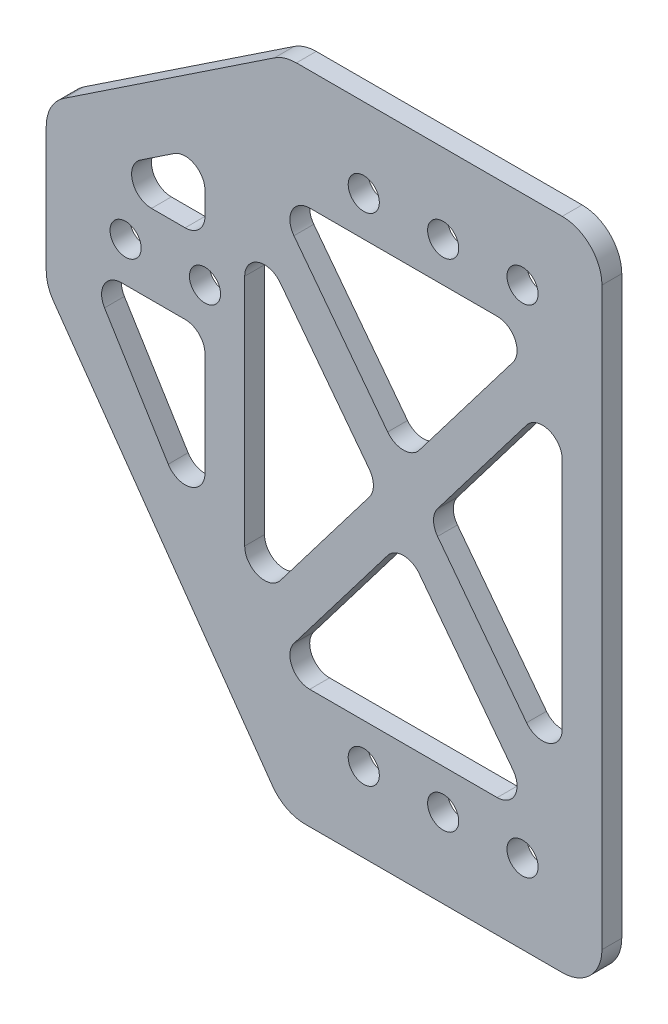
SolidWorks part; units mm, degrees
material "6061-T6 (SS)"
ref_plane "Front Plane" through (0, 0, 0) normal (0, 0, 1) x (1, 0, 0)
ref_plane "Top Plane" through (0, 0, 0) normal (0, 1, 0) x (1, 0, 0)
ref_plane "Right Plane" through (0, 0, 0) normal (1, 0, 0) x (0, 0, -1)
sketch "Sketch1" plane through (0, 0, 0) normal (0, 0, 1) x (1, 0, 0)
  line L0 (0, 25.4) -> (38.1, 50.8)
  line L1 (0, 0) -> (38.1, 0)
  line L2 (0, 0) -> (0, 25.4)
  line L3 (0, 25.4) -> (38.1, 25.4)
  line L4 (38.1, 0) -> (38.1, 25.4)
  line L5 (88.9, 50.8) -> (38.1, 50.8)
  line L6 (88.9, 50.8) -> (88.9, -53.975)
  line L7 (88.9, -53.975) -> (38.1, -53.975)
  line L8 (38.1, 50.8) -> (38.1, -53.975)
  line L9 (38.1, 46.9841) -> (5.7238, 25.4)
  line L10 (0, 0) -> (38.1, -53.975)
  line L11 (3.8863, 0) -> (38.1, -48.4694)
  line L12 (50.8, -41.275) -> (76.2, -41.275) construction
  circle A0 centre (12.7, 12.7) radius 2.4892
  circle A1 centre (25.4, 12.7) radius 2.4892
  circle A5 centre (50.8, 38.1) radius 2.4892
  circle A6 centre (63.5, 38.1) radius 2.4892
  circle A7 centre (76.2, 38.1) radius 2.4892
  circle A8 centre (50.8, -41.275) radius 2.4892
  circle A9 centre (76.2, -41.275) radius 2.4892
  circle A10 centre (63.5, -41.275) radius 2.4892
  circle A11 centre (63.5, 12.7) radius 2.4892 [skipped]
  circle A12 centre (50.8, 12.7) radius 2.4892 [skipped]
  circle A13 centre (38.1, 12.7) radius 2.4892 [skipped]
  point P16 (51.4809, 25.4)
  point P17 (19.05, -26.9875)
  dimension "D3" = 4.9784
  dimension "D4" = 12.7
  dimension "D5" = 12.7
  dimension "D7" = 12.7
  dimension "D10" = 4.9784
  dimension "D12" = 12.7
  dimension "D20" = 12.7
  dimension "D21" = 4.9784
  dimension "D2" = 25.4
  dimension "D8" = 50.8
  dimension "D9" = 25.4
  dimension "D11" = 12.7
  dimension "D13" = 12.7
  dimension "D14" = 12.7
  dimension "D15" = 3.175
  dimension "D16" = 53.975
  dimension "D17" = 3.175
  dimension "D18" = 12.7
  dimension "D19" = 25.4
  dimension "D22" = 38.1
  dimension "D6" = 5
extrude "Boss-Extrude1" add sketch "Sketch1" along normal blind 3.175
fillet "Fillet1" radius 6.35 6 edges at (0, 0, 1.5875) (0, 25.4, 1.5875) (38.1, 50.8, 1.5875) (88.9, -53.975, 1.5875) (38.1, -53.975, 1.5875) (88.9, 50.8, 1.5875)
sketch "Sketch2" plane through (0, 0, 0) normal (0, 0, 1) x (1, 0, 0)
  line L0 (31.75, 31.75) -> (82.55, -34.925) construction
  line L1 (82.55, 31.75) -> (31.75, -34.925) construction
  line L2 (31.75, 26.5111) -> (80.0245, -36.8492)
  line L3 (80.0245, 33.6742) -> (29.2245, -33.0008)
  line L4 (35.7415, 31.75) -> (85.0755, -33.0008)
  line L5 (85.0755, 29.8258) -> (34.2755, -36.8492)
  line L6 (29.2245, 29.8258) -> (80.0245, -36.8492) construction
  line L7 (34.2755, 33.6742) -> (85.0755, -33.0008) construction
  line L8 (31.75, -34.925) -> (6.35, 6.35)
  line L9 (6.35, 6.35) -> (31.75, 6.35)
  line L11 (0, 2.0154) -> (0, 22.0016) construction
  line L12 (25.4, 31.75) -> (25.4, -34.925)
  line L13 (25.4, 19.05) -> (6.35, 19.05)
  line L14 (6.35, 19.05) -> (25.4, 31.75)
  line L33 (88.9, 44.45) -> (88.9, -47.625) construction
  line L34 (31.75, 31.75) -> (82.55, 31.75)
  line L35 (31.75, 31.75) -> (31.75, -34.925)
  line L36 (31.75, -34.925) -> (82.55, -34.925)
  line L37 (82.55, 31.75) -> (82.55, -34.925)
  circle A0 centre (12.7, 12.7) radius 2.4892 construction
  circle A12 centre (76.2, -41.275) radius 2.4892 construction
  circle A13 centre (76.2, 38.1) radius 2.4892 construction
  circle A14 centre (25.4, 12.7) radius 2.4892 construction
  dimension "D3" = 6.35
  dimension "D1" = 6.35
  dimension "D2" = 6.35
  dimension "D4" = 6.35
  dimension "D5" = 6.35
  dimension "D6" = 3.175
  dimension "D7" = 6.35
  dimension "D8" = 6.35
  dimension "D9" = 6.35
  dimension "D10" = 6.35
  dimension "D11" = 6.35
extrude "Cut-Extrude1" cut sketch "Sketch2" along normal through all contours L12 L9 L8 | L2 L35 L3 | L5 L36 L2 | L37 L5 L4 | L34 L4 L3 | L14 L13 L12
fillet "Fillet3" radius 3.175 18 edges at (78.5585, -34.925, 1.5875) (57.15, -6.8264, 1.5875) (35.7415, -34.925, 1.5875) (31.75, 26.5111, 1.5875) (31.75, -29.6861, 1.5875) (53.1585, -1.5875, 1.5875) (35.7415, 31.75, 1.5875) (57.15, 3.6514, 1.5875) (78.5585, 31.75, 1.5875) (82.55, 26.5111, 1.5875) (61.1415, -1.5875, 1.5875) (82.55, -29.6861, 1.5875) (25.4, 6.35, 1.5875) (25.4, -24.6062, 1.5875) (6.35, 6.35, 1.5875) (25.4, 19.05, 1.5875) (25.4, 31.75, 1.5875) (6.35, 19.05, 1.5875)
